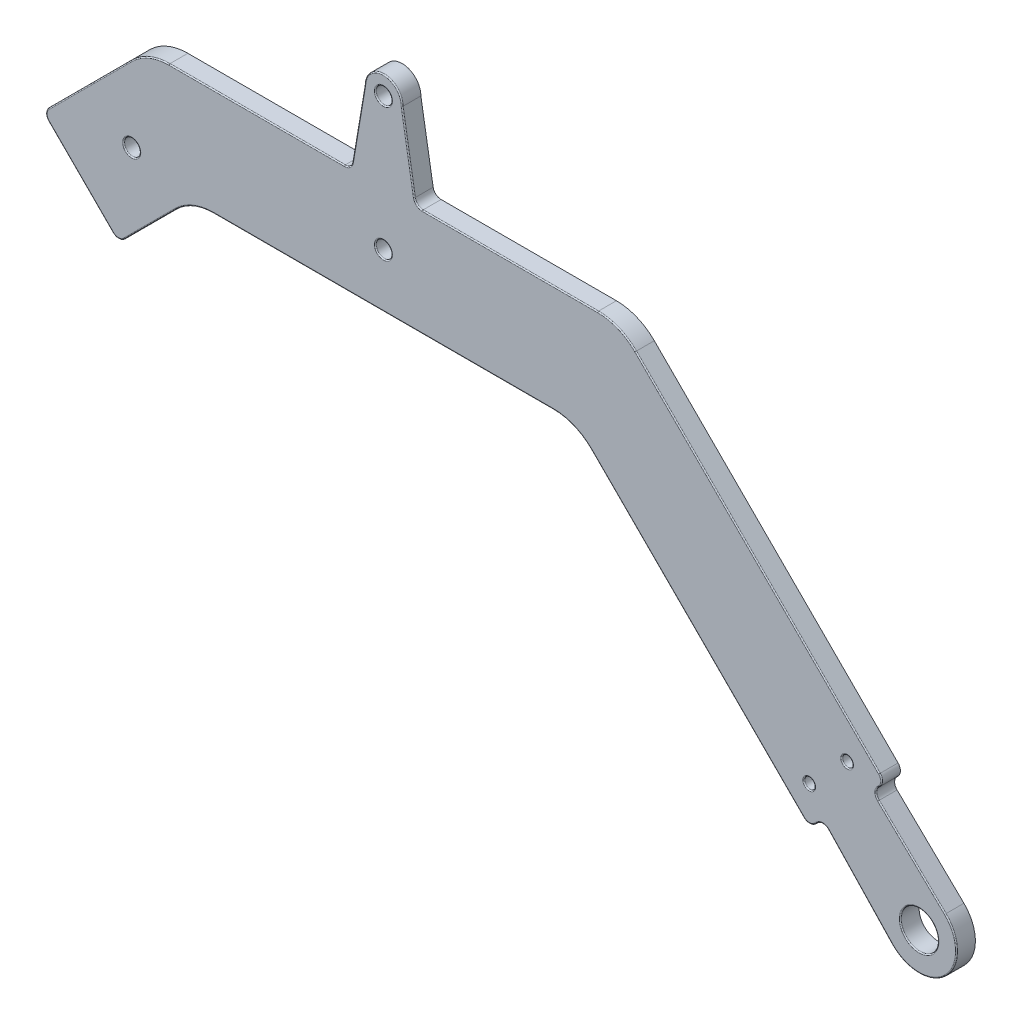
SolidWorks part; units mm, degrees
ref_plane "Front Plane" through (0, 0, 0) normal (0, 0, 1) x (1, 0, 0)
ref_plane "Top Plane" through (0, 0, 0) normal (0, 1, 0) x (1, 0, 0)
ref_plane "Right Plane" through (0, 0, 0) normal (1, 0, 0) x (0, 0, -1)
sketch "Sketch1" plane through (0, 0, 0) normal (0, 0, 1) x (1, 0, 0)
  line L0 (-106.0307, 0) -> (93.9693, 0) construction
  line L1 (-106.0307, 0) -> (-6.0307, 100) construction
  line L2 (-6.0307, 100) -> (93.9693, 0) construction
  line L3 (0, 0) -> (-53.0154, 53.0154) construction
  line L4 (-46.0307, 60) -> (33.9693, 60) construction
  line L5 (-6.0307, 100) -> (-6.0307, 60) construction
  circle A0 centre (-106.0307, 0) radius 20
  circle A1 centre (0, 0) radius 20
  circle A2 centre (93.9693, 0) radius 20
  dimension "D6" = 40
  dimension "D7" = 40
  dimension "D8" = 40
  dimension "D1" = 200
  dimension "D2" = 90
  dimension "D3" = 90
  dimension "D4" = 80
  dimension "D5" = 40
sketch "Sketch2" plane through (0, 0, 0) normal (0, 0, 1) x (1, 0, 0)
  line L0 (-62.5472, 43.4835) -> (-46.0307, 60) construction
  line L2 (-106.0307, 0) -> (-6.0307, 100) construction
  line L3 (-46.0307, 60) -> (33.9693, 60) construction
  line L4 (33.9693, 60) -> (80.5342, 13.435) construction
  line L5 (-6.0307, 100) -> (93.9693, 0) construction
  line L6 (-55.4762, 36.4124) -> (-41.8886, 50)
  line L7 (-41.8886, 50) -> (29.8271, 50)
  line L8 (29.8271, 50) -> (73.4632, 6.364)
  line L9 (-69.6183, 50.5546) -> (-50.1729, 70)
  line L10 (-50.1729, 70) -> (38.1114, 70)
  line L11 (38.1114, 70) -> (87.6053, 20.5061)
  line L12 (-55.4762, 36.4124) -> (-69.6183, 50.5546)
  line L13 (87.6053, 20.5061) -> (73.4632, 6.364)
  line L14 (98.8369, 5.0305) -> (85.2636, 18.1644)
  line L15 (88.8813, -4.8075) -> (76.0143, 8.8101)
  line L16 (85.2636, 18.1644) -> (76.0143, 8.8101)
  line L17 (84.0698, 24.0416) -> (69.9276, 9.8995) construction
  line L18 (-6.0307, 100) -> (-6.0307, 60) construction
  line L19 (-9.5307, 84.85) -> (-12.0307, 70)
  line L20 (-6.0307, 70) -> (-6.0307, 82.2198) construction
  line L21 (-2.5307, 84.85) -> (-0.0307, 70)
  circle A0 centre (93.9693, 0) radius 10 construction
  circle A1 centre (93.9693, 0) radius 3.5
  arc A2 (88.8813, -4.8075) -> (98.8369, 5.0305) centre (93.9693, 0) ccw
  circle A3 centre (93.9693, 0) radius 20 construction
  circle A4 centre (73.4632, 13.435) radius 1
  circle A5 centre (80.5342, 20.5061) radius 1
  circle A6 centre (-6.0307, 60) radius 1.5
  circle A7 centre (-6.0307, 84.85) radius 1.5
  arc A8 (-2.5307, 84.85) -> (-9.5307, 84.85) centre (-6.0307, 84.85) ccw
  circle A9 centre (-53.0154, 53.0154) radius 1.5
  point P45 (-6.0307, 70)
  dimension "D4" = 20
  dimension "D5" = 7
  dimension "D6" = 3
  dimension "D8" = 5
  dimension "D9" = 2
  dimension "D10" = 2
  dimension "D13" = 3
  dimension "D14" = 3
  dimension "D16" = 2
  dimension "D18" = 3
  dimension "D1" = 10
  dimension "D3" = 27.5
  dimension "D7" = 19
  dimension "D11" = 5
  dimension "D12" = 5
  dimension "D15" = 14.85
  dimension "D17" = 6
  dimension "D2" = 10
sketch "Sketch3" plane through (0, 0, 0) normal (0, 0, 1) x (1, 0, 0)
  line L0 (-94.5203, 11.5104) -> (-53.0154, 53.0154) construction
  line L1 (-106.0307, 0) -> (-6.0307, 100) construction
  line L2 (-53.0154, 53.0154) -> (-13.435, 13.435) construction
  line L3 (0, 0) -> (-53.0154, 53.0154) construction
  line L4 (-85.5246, 6.364) -> (-53.0154, 38.8732)
  line L5 (-53.0154, 38.8732) -> (-20.5061, 6.364)
  line L6 (-99.6668, 20.5061) -> (-53.0154, 67.1575)
  line L7 (-53.0154, 67.1575) -> (-6.364, 20.5061)
  line L8 (-95.851, 10.1797) -> (-53.0154, 53.0154) construction
  line L9 (-99.6668, 20.5061) -> (-85.5246, 6.364)
  line L10 (-20.5061, 6.364) -> (-6.364, 20.5061)
  line L11 (-102.9221, 17.2507) -> (-53.0154, 67.1575) construction
  line L12 (-88.78, 3.1086) -> (-53.0154, 38.8732) construction
  line L13 (-110.4492, 4.7673) -> (-96.685, 17.5243)
  line L14 (-106.0307, 0) -> (-96.685, 9.3457) construction
  line L15 (-101.2634, -4.4185) -> (-88.5064, 9.3457)
  line L16 (0, 0) -> (-13.435, 13.435) construction
  line L17 (-4.7673, -4.4185) -> (-17.5243, 9.3457)
  line L18 (4.4185, 4.7673) -> (-9.3457, 17.5243)
  line L19 (-96.1312, 24.0416) -> (-81.9891, 9.8995) construction
  line L20 (-9.8995, 24.0416) -> (-24.0416, 9.8995) construction
  circle A0 centre (-106.0307, 0) radius 10 construction
  circle A1 centre (-106.0307, 0) radius 3.5
  circle A2 centre (0, 0) radius 10 construction
  circle A4 centre (93.9693, 0) radius 10 construction
  circle A6 centre (0, 0) radius 3.5
  circle A7 centre (93.9693, 0) radius 3.5
  circle A8 centre (-106.0307, 0) radius 6.5
  circle A9 centre (0, 0) radius 6.5
  circle A10 centre (93.9693, 0) radius 6.5
  circle A11 centre (-92.5957, 20.5061) radius 1
  circle A12 centre (-85.5246, 13.435) radius 1
  circle A13 centre (-13.435, 20.5061) radius 1
  circle A14 centre (-20.5061, 13.435) radius 1
  circle A16 centre (-53.0154, 53.0154) radius 1.5 construction
  circle A17 centre (-53.0154, 53.0154) radius 1.5
  dimension "D1" = 20
  dimension "D2" = 20
  dimension "D3" = 20
  dimension "D4" = 7
  dimension "D5" = 7
  dimension "D6" = 7
  dimension "D7" = 3
  dimension "D8" = 3
  dimension "D9" = 3
  dimension "D14" = 2
  dimension "D15" = 2
  dimension "D16" = 2
  dimension "D17" = 2
  dimension "D10" = 10
  dimension "D12" = 19
  dimension "D13" = 19
  dimension "D18" = 5
  dimension "D19" = 5
  dimension "D20" = 5
  dimension "D21" = 5
  dimension "D22" = 5
  dimension "D23" = 5
  dimension "D11" = 10
sketch "Sketch4" plane through (0, 0, 0) normal (0, 0, 1) x (1, 0, 0)
  line L0 (-62.7556, 93.8025) -> (52.2444, 93.8025)
  line L1 (52.2444, 93.8025) -> (52.2444, 83.8025)
  line L2 (52.2444, 83.8025) -> (38.1114, 70)
  line L3 (-50.1729, 70) -> (38.1114, 70) construction
  line L4 (38.1114, 70) -> (-54.4235, 70)
  line L5 (-54.4235, 70) -> (-62.7556, 83.8025)
  line L6 (-62.7556, 83.8025) -> (-62.7556, 93.8025)
  line L7 (-2.0307, 60) -> (-2.0307, 70)
  line L8 (-10.0307, 60) -> (-10.0307, 70)
  line L9 (-28.5307, 85.3025) -> (16.4693, 85.3025) construction
  line L10 (-6.0307, 100) -> (-6.0307, 60) construction
  line L12 (-28.5307, 89.8025) -> (16.4693, 89.8025)
  line L13 (-28.5307, 80.8025) -> (16.4693, 80.8025)
  circle A0 centre (-6.0307, 60) radius 1.5 construction
  circle A1 centre (-6.0307, 60) radius 1.5
  arc A2 (-10.0307, 60) -> (-2.0307, 60) centre (-6.0307, 60) ccw
  circle A4 centre (-6.0307, 60) radius 4 construction
  arc A5 (-28.5307, 89.8025) -> (-28.5307, 80.8025) centre (-28.5307, 85.3025) ccw
  arc A6 (16.4693, 80.8025) -> (16.4693, 89.8025) centre (16.4693, 85.3025) ccw
  point P18 (-2.0307, 60)
  point P24 (-6.0307, 85.3025)
  dimension "D1" = 115
  dimension "D2" = 10
  dimension "D4" = 45
  dimension "D5" = 9
  dimension "D6" = 4
  dimension "D3" = 2.5
sketch "Sketch5" plane through (0, 0, 0) normal (0, 0, 1) x (1, 0, 0)
  line L0 (-2.5307, 84.85) -> (-0.0307, 70) construction
  line L1 (-9.5307, 84.85) -> (-12.0307, 70) construction
  line L2 (-2.5307, 84.85) -> (-0.0307, 70)
  line L3 (98.8369, 5.0305) -> (85.2636, 18.1644)
  line L4 (85.2636, 18.1644) -> (76.0143, 8.8101)
  line L5 (76.0143, 8.8101) -> (88.8813, -4.8075)
  line L6 (98.8369, 5.0305) -> (85.2636, 18.1644)
  line L8 (76.0143, 8.8101) -> (88.8813, -4.8075)
  line L9 (-9.5307, 84.85) -> (-12.0307, 70)
  line L10 (-12.0307, 70) -> (-50.1729, 70)
  line L11 (73.4632, 6.364) -> (76.0143, 8.8101)
  line L14 (38.1114, 70) -> (-50.1729, 70)
  line L15 (87.6053, 20.5061) -> (38.1114, 70)
  line L16 (73.4632, 6.364) -> (87.6053, 20.5061)
  line L17 (29.8271, 50) -> (73.4632, 6.364)
  line L18 (-41.8886, 50) -> (29.8271, 50)
  line L19 (-55.4762, 36.4124) -> (-41.8886, 50)
  line L20 (-69.6183, 50.5546) -> (-55.4762, 36.4124)
  line L21 (-50.1729, 70) -> (-69.6183, 50.5546)
  line L22 (38.1114, 70) -> (-0.0307, 70)
  line L23 (87.6053, 20.5061) -> (38.1114, 70)
  line L24 (85.2636, 18.1644) -> (87.6053, 20.5061)
  line L25 (29.8271, 50) -> (73.4632, 6.364)
  line L26 (-41.8886, 50) -> (29.8271, 50)
  line L27 (-55.4762, 36.4124) -> (-41.8886, 50)
  line L28 (-69.6183, 50.5546) -> (-55.4762, 36.4124)
  line L29 (-50.1729, 70) -> (-69.6183, 50.5546)
  arc A0 (-2.5307, 84.85) -> (-9.5307, 84.85) centre (-6.0307, 84.85) ccw construction
  circle A1 centre (93.9693, 0) radius 3.5
  circle A2 centre (93.9693, 0) radius 3.5
  arc A3 (88.8813, -4.8075) -> (98.8369, 5.0305) centre (93.9693, 0) ccw
  arc A4 (88.8813, -4.8075) -> (98.8369, 5.0305) centre (93.9693, 0) ccw
  circle A5 centre (-53.0154, 53.0154) radius 1.5
  circle A6 centre (-53.0154, 53.0154) radius 1.5
  circle A7 centre (-6.0307, 84.85) radius 1.5
  circle A8 centre (-6.0307, 84.85) radius 1.5
  circle A9 centre (-6.0307, 60) radius 1.5
  circle A10 centre (-6.0307, 60) radius 1.5
  circle A11 centre (80.5342, 20.5061) radius 1
  circle A12 centre (80.5342, 20.5061) radius 1
  circle A13 centre (73.4632, 13.435) radius 1
  circle A14 centre (73.4632, 13.435) radius 1
  arc A15 (-2.5307, 84.85) -> (-9.5307, 84.85) centre (-6.0307, 84.85) ccw
  dimension "D1" = 0
  dimension "D2" = 0
  dimension "D3" = 0
  dimension "D4" = 0
  dimension "D5" = 0
  dimension "D6" = 0
  dimension "D7" = 0
  dimension "D8" = 0
extrude "Boss-Extrude1" add sketch "Sketch5" along normal blind 3.5
fillet "Fillet1" radius 10 4 edges at (29.8271, 50, 1.75) (-41.8886, 50, 1.75) (-50.1729, 70, 1.75) (38.1114, 70, 1.75)
fillet "Fillet2" radius 1.5 8 edges at (-55.4762, 36.4124, 1.75) (-69.6183, 50.5546, 1.75) (-12.0307, 70, 1.75) (-0.0307, 70, 1.75) (73.4632, 6.364, 1.75) (76.0143, 8.8101, 1.75) (85.2636, 18.1644, 1.75) (87.6053, 20.5061, 1.75)
fillet "Fillet3" radius 0.2 34 edges at (74.4632, 13.435, 3.5) (-4.5307, 60, 3.5) (-51.5154, 53.0154, 3.5) (-68.997, 50.5546, 3.5) (-60.8297, 59.3431, 3.5) (-49.8576, 69.2388, 3.5) (-29.665, 70, 3.5) (-12.3307, 70.3547, 3.5) (-10.6754, 78.0505, 3.5) (-6.0307, 88.35, 3.5) (-1.386, 78.0505, 3.5) (0.2692, 70.3547, 3.5) (17.6036, 70, 3.5) (37.7961, 69.2388, 3.5) (63.7925, 44.3189, 3.5) (86.984, 20.5061, 3.5) (86.4432, 19.344, 3.5) (85.9025, 18.1696, 3.5) (92.5982, 11.0673, 3.5) (98.8895, -4.9791, 3.5) (82.9667, 1.4521, 3.5) (75.9988, 8.1812, 3.5) (74.7235, 7.5724, 3.5) (73.4695, 6.9633, 3.5) (52.5903, 27.2368, 3.5) (29.5118, 49.2388, 3.5) (-6.0307, 50, 3.5) (-41.5733, 49.2388, 3.5) (-49.6165, 42.2721, 3.5) (-55.4762, 37.0337, 3.5) (-62.5472, 43.4835, 3.5) (97.4693, 0, 3.5) (-4.5307, 84.85, 3.5) (81.5342, 20.5061, 3.5)
